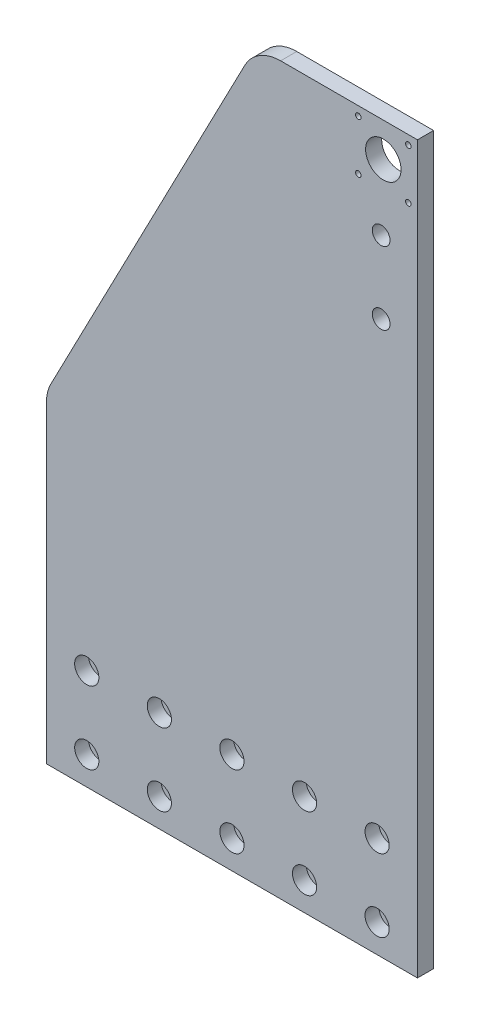
SolidWorks part; units mm, degrees
material "1.0037 (S235JR)"
ref_plane "Ön Düzlem" through (0, 0, 0) normal (0, 0, 1) x (1, 0, 0)
ref_plane "Üst Düzlem" through (0, 0, 0) normal (0, 1, 0) x (1, 0, 0)
ref_plane "Sağ Düzlem" through (0, 0, 0) normal (1, 0, 0) x (0, 0, -1)
sketch "Sketch1" plane through (0, 0, 0) normal (0, 0, 1) x (1, 0, 0)
  line L8 (-115, 200) -> (-115, 0)
  line L10 (-115, 0) -> (115, 0)
  line L12 (-115, 200) -> (15, 450)
  line L13 (15, 450) -> (115, 450)
  line L14 (115, 450) -> (115, 0)
  dimension "D1" = 230
  dimension "D2" = 450
  dimension "D3" = 200
  dimension "D4" = 100
extrude "Boss-Extrude1" add sketch "Sketch1" along normal mid plane 10
hole_wizard "CBORE for M8 Hex Socket Head Cap Screw1" positions "Sketch2" profile "Sketch3" counterbore size "M8" standard "ISO" end condition through all
sketch "Sketch2" plane through (0, 0, 5) normal (0, 0, 1) x (1, 0, 0)
  line L0 (-115, 200) -> (-115, 0) construction
  line L2 (115, 0) -> (115, 450) construction
  point P2 (-90, 17.5)
  point P4 (-45, 17.5)
  point P6 (45, 17.5)
  point P8 (90, 17.5)
  point P10 (0, 17.5)
  point P34 (-90, 62.5)
  point P35 (-45, 62.5)
  point P36 (45, 62.5)
  point P37 (90, 62.5)
  point P38 (0, 62.5)
  dimension "D1" = 17.5
  dimension "D2" = 25
  dimension "D3" = 25
  dimension "D4" = 45
  dimension "D5" = 45
  dimension "D6" = 45
  dimension "D7" = 2
  dimension "D8" = 45
sketch "Sketch3" plane through (-90, 17.5, 5) normal (1, 0, 0) x (0, -1, 0)
  line L0 (0, 0) -> (0, 10)
  line L1 (0, 10) -> (4.5, 10)
  line L3 (4.5, 10) -> (4.5, 8.6)
  line L4 (4.5, 8.6) -> (7.5, 8.6)
  line L5 (7.5, 8.6) -> (7.5, 0)
  line L7 (7.5, 0) -> (0, 0)
  line L11 (0, -6.35) -> (0, 107.95) construction
  dimension "Thru Hole Dia." = 9
  dimension "Thru Hole Depth" = 10
  dimension "C'Bore Dia." = 15
  dimension "C'Bore Depth" = 8.6
sketch "Sketch4" plane through (-115, 0, 0) normal (-1, 0, 0) x (0, 0, 1)
  line L0 (-5, 200) -> (-5, 0) construction
  line L1 (-5, 125) -> (-1.5, 125)
  line L2 (-5, 125) -> (-5, 95)
  line L3 (-5, 95) -> (-1.5, 95)
  line L4 (-1.5, 125) -> (-1.5, 95)
  line L5 (5, 0) -> (-5, 0) construction
  dimension "D1" = 30
  dimension "D2" = 95
  dimension "D3" = 3.5
extrude "Cut-Extrude1" [suppressed] cut sketch "Sketch4" against normal through all
sketch "Sketch5" plane through (0, 0, 5) normal (0, 0, 1) x (1, 0, 0)
  line L0 (115, 0) -> (115, 450) construction
  line L1 (115, 450) -> (15, 450) construction
  circle A0 centre (93.85, 428.85) radius 11
  dimension "D3" = 22
  dimension "D1" = 21.15
  dimension "D2" = 21.15
extrude "Cut-Extrude2" cut sketch "Sketch5" against normal through all contours A0
hole_wizard "CBORE for M3 Hex Socket Head Cap Screw1" positions "Sketch6" profile "Sketch7" counterbore size "M3" standard "ISO" end condition through all
sketch "Sketch6" plane through (0, 0, -5) normal (0, 0, 1) x (1, 0, 0)
  point P0 (109.35, 444.35)
  point P3 (78.35, 444.35)
  point P6 (78.35, 413.35)
  point P9 (109.35, 413.35)
sketch "Sketch7" plane through (109.35, 444.35, -5) normal (1, 0, 0) x (0, 1, 0)
  line L0 (0, 0) -> (0, 10)
  line L1 (0, 10) -> (1.7, 10)
  line L3 (1.7, 10) -> (1.7, 3.4)
  line L4 (1.7, 3.4) -> (3.25, 3.4)
  line L5 (3.25, 3.4) -> (3.25, 0)
  line L7 (3.25, 0) -> (0, 0)
  line L11 (0, -6.35) -> (0, 107.95) construction
  dimension "Thru Hole Dia." = 3.4
  dimension "Thru Hole Depth" = 10
  dimension "C'Bore Dia." = 6.5
  dimension "C'Bore Depth" = 3.4
fillet "Fillet1" radius 25 2 edges at (15, 450, 0) (-115, 200, 0)
sketch "Sketch8" plane through (0, 0, 5) normal (0, 0, 1) x (1, 0, 0)
  line L0 (115, 450) -> (30.178, 450) construction
  line L1 (115, 0) -> (115, 450) construction
  circle A0 centre (92.5, 387.5) radius 4.5
  circle A1 centre (92.5, 342.5) radius 4.5
  dimension "D4" = 9
  dimension "D1" = 62.5
  dimension "D2" = 45
  dimension "D3" = 22.5
hole_wizard "M10 Clearance Hole1" positions "Sketch9" profile "Sketch10" hole size "M10" standard "ISO"
sketch "Sketch9" plane through (0, 0, 5) normal (0, 0, 1) x (1, 0, 0)
  point P0 (92.5, 387.5)
  point P3 (92.5, 342.5)
sketch "Sketch10" plane through (92.5, 387.5, 5) normal (1, 0, 0) x (0, -1, 0)
  line L0 (0, 0) -> (0, 28.3047)
  line L1 (0, 28.3047) -> (5.5, 25)
  line L2 (5.5, 25) -> (5.5, 0)
  line L5 (5.5, 0) -> (0, 0)
  line L10 (0, 28.3047) -> (-5.5, 25) construction
  line L11 (0, -6.35) -> (0, 107.95) construction
  dimension "Hole Dia." = 11
  dimension "Hole Depth" = 25
  dimension "Drill Angle" = 118
